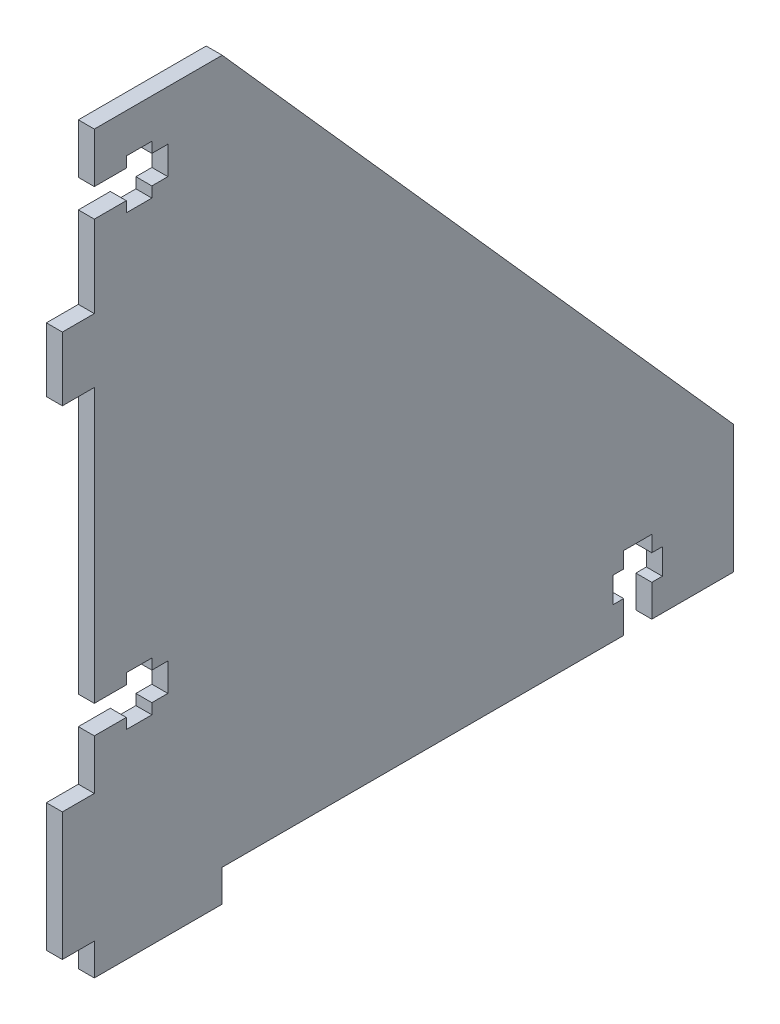
SolidWorks part; units mm, degrees
ref_plane "Front Plane" through (0, 0, 0) normal (0, 0, 1) x (1, 0, 0)
ref_plane "Top Plane" through (0, 0, 0) normal (0, 1, 0) x (1, 0, 0)
ref_plane "Right Plane" through (0, 0, 0) normal (1, 0, 0) x (0, 0, -1)
sketch "Sketch1" plane through (0, 0, 0) normal (1, 0, 0) x (0, 0, -1)
  line L0 (20, 110) -> (100, 20)
  line L1 (20, 0) -> (100, 0)
  line L2 (0, 0) -> (0, 110)
  line L3 (0, 110) -> (20, 110)
  line L4 (100, 0) -> (100, 20)
  line L5 (0, 0) -> (100, 0) construction
  line L6 (0, 97.8) -> (9, 103.85) construction
  line L7 (0, 0) -> (0, -5)
  line L8 (0, -5) -> (20, -5)
  line L9 (20, 0) -> (20, -5)
  line L10 (0, 102.2) -> (5, 102.2)
  line L11 (0, 32.2) -> (5, 32.2)
  line L12 (0, 27.8) -> (5, 27.8)
  line L13 (5, 32.2) -> (5, 27.8)
  line L14 (0, 102.2) -> (0, 97.8)
  line L15 (0, 97.8) -> (5, 97.8)
  line L16 (5, 102.2) -> (5, 97.8)
  line L17 (0, 20) -> (-5, 20)
  line L18 (0, 20) -> (0, 0)
  line L19 (0, 0) -> (-5, 0)
  line L20 (-5, 20) -> (-5, 0)
  line L21 (5, 103.85) -> (9, 103.85)
  line L22 (5, 103.85) -> (5, 96.15)
  line L23 (5, 96.15) -> (9, 96.15)
  line L24 (9, 103.85) -> (9, 96.15)
  line L25 (0, 102.2) -> (9, 96.15) construction
  line L26 (5, 96.15) -> (11.5, 102.2) construction
  line L27 (9, 102.2) -> (11.5, 102.2)
  line L28 (9, 102.2) -> (9, 97.8)
  line L29 (9, 97.8) -> (11.5, 97.8)
  line L30 (11.5, 102.2) -> (11.5, 97.8)
  line L31 (3.2727, 100) -> (9.1364, 100) construction
  line L32 (5, 103.85) -> (11.5, 97.8) construction
  line L33 (5, 33.85) -> (9, 33.85)
  line L34 (5, 33.85) -> (5, 26.15)
  line L35 (5, 26.15) -> (9, 26.15)
  line L36 (9, 33.85) -> (9, 26.15)
  line L37 (9, 32.2) -> (11.5, 32.2)
  line L38 (9, 32.2) -> (9, 27.8)
  line L39 (9, 27.8) -> (11.5, 27.8)
  line L40 (11.5, 32.2) -> (11.5, 27.8)
  line L41 (0, 27.8) -> (9, 33.85) construction
  line L42 (0, 32.2) -> (9, 26.15) construction
  line L43 (5, 26.15) -> (11.5, 32.2) construction
  line L44 (3.2727, 30) -> (9.1364, 30) construction
  line L45 (5, 33.85) -> (11.5, 27.8) construction
  line L46 (0, 102.2) -> (0, 32.2) construction
  line L47 (81.15, 9) -> (87.2, 0) construction
  line L48 (82.8, 0) -> (87.2, 0)
  line L49 (82.8, 0) -> (82.8, 5)
  line L50 (82.8, 5) -> (87.2, 5)
  line L51 (87.2, 0) -> (87.2, 5)
  line L52 (81.15, 9) -> (88.85, 9)
  line L53 (81.15, 9) -> (81.15, 5)
  line L54 (81.15, 5) -> (88.85, 5)
  line L55 (88.85, 9) -> (88.85, 5)
  line L56 (82.8, 0) -> (88.85, 9) construction
  line L57 (81.15, 5) -> (87.2, 11.5) construction
  line L58 (82.8, 11.5) -> (87.2, 11.5)
  line L59 (82.8, 11.5) -> (82.8, 9)
  line L60 (82.8, 9) -> (87.2, 9)
  line L61 (87.2, 11.5) -> (87.2, 9)
  line L62 (88.85, 5) -> (82.8, 11.5) construction
  line L63 (85, 3.2727) -> (85, 9.1364) construction
  line L65 (0, 85) -> (-5, 85)
  line L66 (0, 85) -> (0, 75)
  line L67 (0, 75) -> (-5, 75)
  line L68 (-5, 85) -> (-5, 75)
  dimension "D1" = 100
  dimension "D2" = 110
  dimension "D3" = 20
  dimension "D4" = 20
  dimension "D5" = 5
  dimension "D6" = 5
  dimension "D7" = 20
  dimension "D8" = 5
  dimension "D9" = 4.4
  dimension "D10" = 10
  dimension "D11" = 20
  dimension "D12" = 2
  dimension "D13" = 7.7
  dimension "D14" = 4
  dimension "D15" = 4.4
  dimension "D16" = 2.5
  dimension "D17" = 70
  dimension "D18" = 5
  dimension "D19" = 4.4
  dimension "D20" = 7.7
  dimension "D21" = 4
  dimension "D22" = 2.5
  dimension "D23" = 4.4
  dimension "D24" = 15
  dimension "D25" = 5
  dimension "D26" = 10
  dimension "D27" = 25
  dimension "D28" = 10
extrude "Boss-Extrude1" add sketch "Sketch1" along normal blind 2.5 contours L58 L61 L52 L55 L54 L51 L1 L4 L0 L3 L2 L10 L22 L21 L24 L27 L30 L29 L23 L15 L11 L34 L33 L36 L37 L40 L39 L35 L12 L17 L20 L19 L7 L8 L9 L49 L53 L59 | L17 L20 L19 L2 | L65 L68 L67 L2
